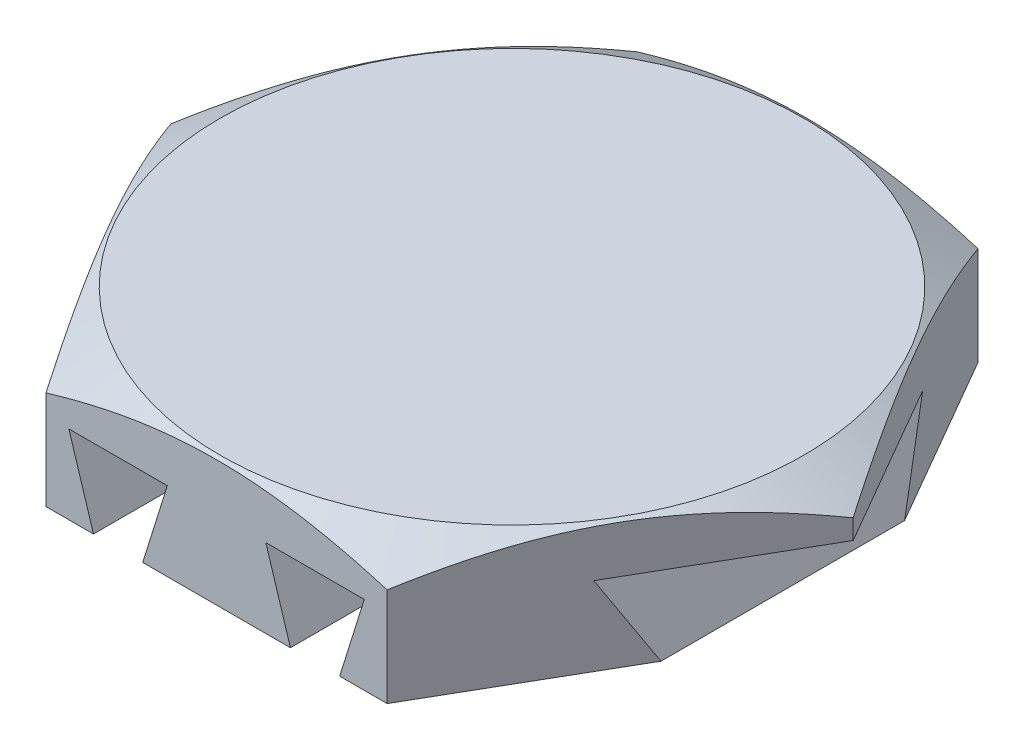
SolidWorks part; units mm, degrees
ref_plane "前基準面" through (0, 0, 0) normal (0, 0, 1) x (1, 0, 0)
ref_plane "上基準面" through (0, 0, 0) normal (0, 1, 0) x (1, 0, 0)
ref_plane "右基準面" through (0, 0, 0) normal (1, 0, 0) x (0, 0, -1)
sketch "草圖1" plane through (0, 0, 0) normal (0, 1, 0) x (1, 0, 0)
  line L0 (-34.641, 0) -> (-30, 0)
  line L1 (17.3205, -30) -> (34.641, 0)
  line L2 (34.641, 0) -> (17.3205, 30)
  line L3 (17.3205, 30) -> (-17.3205, 30)
  line L4 (-17.3205, 30) -> (-34.641, 0)
  line L5 (-34.641, 0) -> (-17.3205, -30)
  line L6 (-17.3205, -30) -> (17.3205, -30)
  line L7 (30, 0) -> (34.641, 0)
  circle A0 centre (0, 0) radius 30 construction
  dimension "D1" = 60
extrude "填料-伸長1" add sketch "草圖1" along normal blind 13
sketch "草圖2" plane through (0, 0, 0) normal (0, 0, 1) x (1, 0, 0)
  line L0 (0, 13) -> (0, 0) construction
  line L1 (-17.3205, 13) -> (17.3205, 13) construction
  line L2 (-7.5, 0) -> (-5, 8)
  line L3 (-17.3205, 0) -> (17.3205, 0) construction
  line L4 (-5, 8) -> (5, 8)
  line L5 (5, 8) -> (7.5, 0)
  line L6 (7.5, 0) -> (-7.5, 0)
  line L7 (27.5, 0) -> (12.5, 0)
  line L8 (12.5, 0) -> (15, 8)
  line L9 (15, 8) -> (25, 8)
  line L10 (25, 8) -> (27.5, 0)
  line L11 (-12.5, 0) -> (-27.5, 0)
  line L12 (-27.5, 0) -> (-25, 8)
  line L13 (-25, 8) -> (-15, 8)
  line L14 (-15, 8) -> (-12.5, 0)
  line L15 (-27.5, 0) -> (-12.5, 0) construction
  line L16 (-20, 0) -> (-20, 13) construction
  line L17 (-34.641, 13) -> (-17.3205, 13) construction
  line L18 (-27.5, 0) -> (-12.5, 0)
  line L19 (-25, 8) -> (-15, 8)
  line L20 (-34.641, 8) -> (34.641, 8)
  line L21 (-34.641, 13) -> (-34.641, 0) construction
  line L22 (34.641, 13) -> (34.641, 0) construction
  line L23 (34.641, 8) -> (34.641, 0)
  line L24 (34.641, 0) -> (-34.641, 0)
  line L25 (-34.641, 0) -> (-34.641, 8)
  line L26 (12.5, 0) -> (27.5, 0) construction
  line L27 (20, 0) -> (20, 8) construction
  point P9 (0, 8)
  point P14 (0, 0)
  point P25 (-20, 8)
  dimension "D1" = 10
  dimension "D2" = 15
  dimension "D3" = 8
  dimension "D6" = 20
  dimension "D7" = 20
  dimension "D4" = 2
  dimension "D5" = 2
extrude "除料-伸長1" cut sketch "草圖2" against normal through all both and the other way through all contours L24 L2 L20 L14 | L25 L24 L12 L20 | L24 L8 L20 L5 | L24 L23 L20 L10
sketch "草圖3" plane through (0, 0, 0) normal (0, 0, 1) x (1, 0, 0)
  line L0 (0, 13.801) -> (0, 0) construction
  line L1 (0, 10) -> (-22.5, 10)
  line L2 (-22.5, 10) -> (-20, 0)
  line L3 (-17.3205, 0) -> (-27.5, 0) construction
  line L4 (-20, 0) -> (0, 0)
  line L5 (0, 0) -> (0, 10)
  dimension "D1" = 22.5
  dimension "D2" = 20
  dimension "D3" = 10
revolve "除料-旋轉1" cut sketch "草圖3" angle 360 about L0
sketch "草圖4" plane through (0, 0, 0) normal (0, 0, 1) x (1, 0, 0)
  line L1 (34.641, 13) -> (-34.641, 13)
  line L2 (34.641, 13) -> (34.641, 10)
  line L3 (34.641, 10) -> (-34.641, 10)
  line L4 (-34.641, 13) -> (-34.641, 10)
  line L5 (-34.641, 13) -> (-34.641, 8) construction
  line L8 (0, 13) -> (0, -0.3622) construction
  line L10 (34.641, 13) -> (0, 13)
  line L11 (0, 13) -> (0, 10)
  line L12 (0, 10) -> (34.641, 10)
  line L14 (0, 10) -> (20, 10)
  line L15 (20, 10) -> (0, 10)
  line L17 (0, 10) -> (-20, 10)
  line L19 (34.641, 13) -> (29.641, 13)
  line L20 (-34.641, 13) -> (-29.641, 13)
  line L21 (29.641, 13) -> (34.641, 10)
  line L22 (-29.641, 13) -> (-34.641, 10)
  line L23 (20, 10) -> (17.5, 10)
  line L24 (-20, 10) -> (-17.5, 10)
  line L25 (29.641, 13) -> (0, 13)
  line L26 (0, 13) -> (-29.641, 13)
  dimension "D1" = 3
  dimension "D2" = 20
  dimension "D3" = 20
  dimension "D4" = 5
  dimension "D5" = 5
  dimension "D6" = 2.5
  dimension "D7" = 2.5
revolve "除料-旋轉7" cut sketch "草圖4" angle 360 about L8
